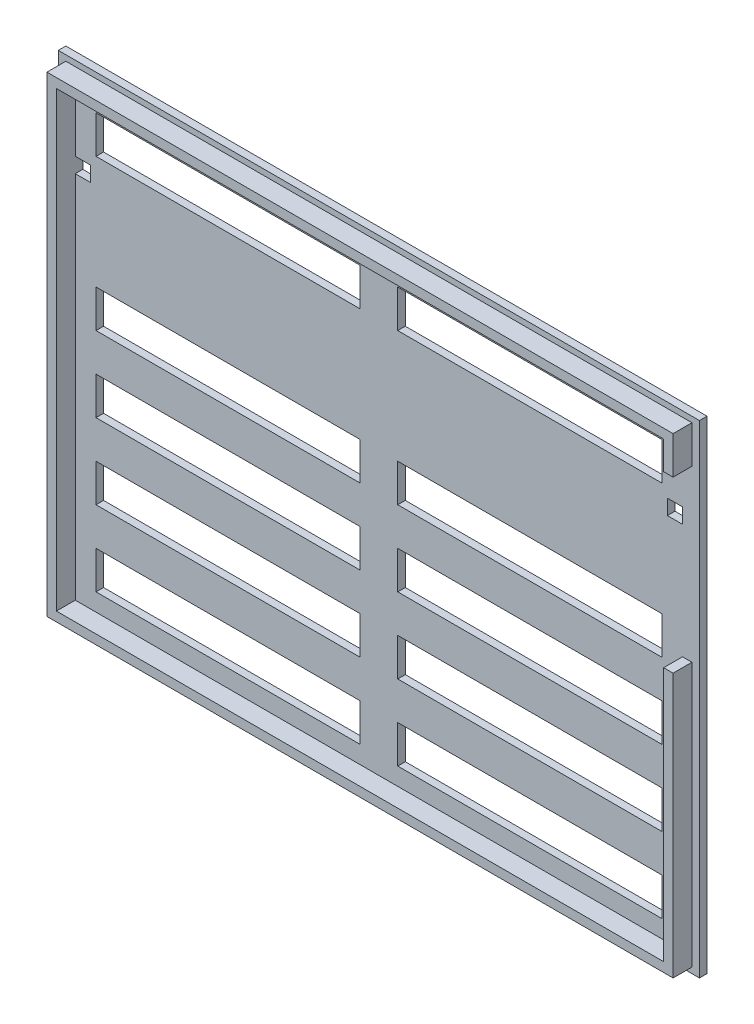
SolidWorks part; units mm, degrees
ref_plane "前视基准面" through (0, 0, 0) normal (0, 0, 1) x (1, 0, 0)
ref_plane "上视基准面" through (0, 0, 0) normal (0, 1, 0) x (1, 0, 0)
ref_plane "右视基准面" through (0, 0, 0) normal (1, 0, 0) x (0, 0, -1)
sketch "草图3" plane through (0, 0, 0) normal (0, 0, 1) x (1, 0, 0)
  line L1 (-85, 64) -> (85, 64)
  line L2 (-85, 64) -> (-85, -64)
  line L3 (-85, -64) -> (85, -64)
  line L4 (85, 64) -> (85, -64)
  line L5 (-85, 64) -> (85, -64) construction
  line L6 (-85, -64) -> (85, 64) construction
  point P0 (0, 0)
  dimension "D1" = 170
  dimension "D2" = 128
extrude "凸台-拉伸2" add sketch "草图3" along normal blind 2
sketch "草图4" plane through (0, 0, 2) normal (0, 0, 1) x (1, 0, 0)
  line L1 (-83, 62.5) -> (83, 62.5)
  line L2 (-83, 62.5) -> (-83, -62.5)
  line L3 (-83, -62.5) -> (83, -62.5)
  line L4 (83, 62.5) -> (83, -62.5)
  line L5 (-83, 62.5) -> (83, -62.5) construction
  line L6 (-83, -62.5) -> (83, 62.5) construction
  point P0 (0, 0)
  dimension "D1" = 166
  dimension "D2" = 125
extrude "凸台-拉伸3" add sketch "草图4" along normal blind 5
sketch "草图5" plane through (0, 0, 7) normal (0, 0, 1) x (1, 0, 0)
  line L1 (-80.5, 60) -> (80.5, 60)
  line L2 (-80.5, 60) -> (-80.5, -60)
  line L3 (-80.5, -60) -> (80.5, -60)
  line L4 (80.5, 60) -> (80.5, 52.5)
  line L5 (-80.5, 60) -> (80.5, -60) construction
  line L6 (-80.5, -60) -> (80.5, 60) construction
  line L8 (83, -62.5) -> (83, 62.5) construction
  line L9 (80.5, 52.5) -> (83, 52.5)
  line L11 (80.5, 7.5) -> (83, 7.5)
  line L12 (83, 52.5) -> (83, 7.5)
  line L13 (83, 62.5) -> (-83, 62.5) construction
  line L14 (80.5, 7.5) -> (80.5, -60)
  point P0 (0, 0)
  dimension "D1" = 161
  dimension "D2" = 120
  dimension "D3" = 10
  dimension "D4" = 45
extrude "切除-拉伸1" cut sketch "草图5" against normal blind 5
sketch "草图6" plane through (0, 0, 0) normal (0, 0, -1) x (-1, 0, 0)
  line L0 (-85, 64) -> (85, 64) construction
  line L1 (-80.5, 41.93) -> (-76.5, 41.93)
  line L2 (-80.5, 41.93) -> (-80.5, 37.93)
  line L3 (-80.5, 37.93) -> (-76.5, 37.93)
  line L4 (-76.5, 41.93) -> (-76.5, 37.93)
  line L5 (76.5, 41.93) -> (80.5, 41.93)
  line L6 (76.5, 41.93) -> (76.5, 37.93)
  line L7 (76.5, 37.93) -> (80.5, 37.93)
  line L8 (80.5, 41.93) -> (80.5, 37.93)
  line L9 (-85, -64) -> (-85, 64) construction
  line L10 (85, 64) -> (85, -64) construction
  dimension "D1" = 4
  dimension "D2" = 4
  dimension "D3" = 4
  dimension "D4" = 4
  dimension "D5" = 22.07
  dimension "D6" = 22.07
  dimension "D7" = 153
  dimension "D8" = 4.5
  dimension "D9" = 4.5
sketch "草图7" plane through (0, 0, 2) normal (0, 0, 1) x (1, 0, 0)
  line L0 (-80.5, 60) -> (-80.5, -60) construction
  line L1 (-75, -55.3371) -> (-5, -55.3371)
  line L2 (-75, -55.3371) -> (-75, -45.3371)
  line L3 (-75, -45.3371) -> (-5, -45.3371)
  line L4 (75, -55.3371) -> (75, -45.3371)
  line L5 (80.5, -60) -> (80.5, 7.5) construction
  line L6 (-75, -35.3371) -> (-75, -25.3371)
  line L7 (-75, -35.3371) -> (-5, -35.3371)
  line L8 (75, -35.3371) -> (75, -25.3371)
  line L9 (-75, -25.3371) -> (-5, -25.3371)
  line L10 (-75, -15.3371) -> (-75, -5.3371)
  line L11 (-75, -15.3371) -> (-5, -15.3371)
  line L12 (75, -15.3371) -> (75, -5.3371)
  line L13 (-75, -5.3371) -> (-5, -5.3371)
  line L14 (-75, 4.6629) -> (-75, 14.6629)
  line L15 (-75, 4.6629) -> (-5, 4.6629)
  line L16 (75, 4.6629) -> (75, 14.6629)
  line L17 (-75, 14.6629) -> (-5, 14.6629)
  line L22 (-75, 44.6629) -> (-75, 54.6629)
  line L23 (-75, 44.6629) -> (-5, 44.6629)
  line L24 (75, 44.6629) -> (75, 54.6629)
  line L25 (-75, 54.6629) -> (-5, 54.6629)
  line L26 (-75, -55.3371) -> (-75, -35.3371) construction
  line L27 (5, 54.6629) -> (75, 54.6629)
  line L29 (-5, 54.6629) -> (-5, 44.6629)
  line L31 (5, 54.6629) -> (5, 44.6629)
  line L32 (5, 44.6629) -> (75, 44.6629)
  line L35 (5, 14.6629) -> (75, 14.6629)
  line L36 (5, 4.6629) -> (75, 4.6629)
  line L37 (5, -5.3371) -> (75, -5.3371)
  line L38 (5, -15.3371) -> (75, -15.3371)
  line L39 (5, -25.3371) -> (75, -25.3371)
  line L40 (5, -35.3371) -> (75, -35.3371)
  line L41 (5, -45.3371) -> (75, -45.3371)
  line L42 (5, -55.3371) -> (75, -55.3371)
  line L45 (5, 14.6629) -> (5, 4.6629)
  line L46 (-5, 14.6629) -> (-5, 4.6629)
  line L47 (5, -5.3371) -> (5, -15.3371)
  line L48 (-5, -5.3371) -> (-5, -15.3371)
  line L49 (5, -25.3371) -> (5, -35.3371)
  line L50 (-5, -25.3371) -> (-5, -35.3371)
  line L51 (5, -45.3371) -> (5, -55.3371)
  line L52 (-5, -45.3371) -> (-5, -55.3371)
  line L53 (-75, 34.6629) -> (-5, 34.6629) [skipped]
  line L54 (-75, 24.6629) -> (-5, 24.6629) [skipped]
  line L55 (-75, 24.6629) -> (-75, 34.6629) [skipped]
  line L56 (75, 24.6629) -> (75, 34.6629) [skipped]
  dimension "D1" = 150
  dimension "D2" = 10
  dimension "D3" = 5.5
  dimension "D4" = 5.5
  dimension "D6" = 20
  dimension "D5" = 6
extrude "切除-拉伸3" cut sketch "草图7" against normal through all
extrude "切除-拉伸4" cut sketch "草图6" against normal through all
